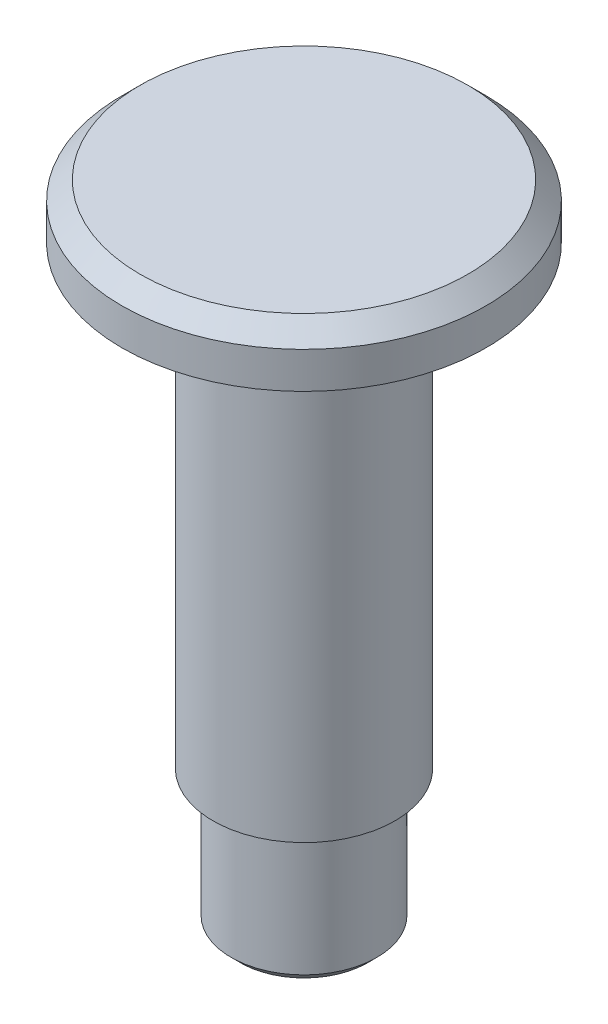
SolidWorks part; units mm, degrees
ref_plane "Plan1" through (0, 0, 0) normal (0, 0, 1) x (1, 0, 0)
ref_plane "Plan2" through (0, 0, 0) normal (0, 1, 0) x (1, 0, 0)
ref_plane "Plan3" through (0, 0, 0) normal (1, 0, 0) x (0, 0, -1)
sketch "Esquisse1" plane through (0, 0, 0) normal (0, 0, 1) x (1, 0, 0)
  line L0 (0, 0) -> (0, 100) construction
  line L1 (0, 0) -> (3.5, 0)
  line L2 (4, 0.5) -> (4, 7.5)
  line L3 (5, 7.5) -> (5, 32.5)
  line L4 (5.6, 32.5) -> (10, 32.5)
  line L5 (10, 34.5) -> (10, 32.5)
  line L7 (9, 35.5) -> (0, 35.5)
  line L8 (0, 35.5) -> (0, 0)
  line L9 (5, 7.5) -> (4.6, 7.5)
  line L10 (9, 35.5) -> (10, 34.5)
  line L11 (3.5, 0) -> (4, 0.5)
  arc A0 (4.6, 7.5) -> (4, 7.5) centre (4.3, 7.5) ccw
  arc A1 (5.6, 32.5) -> (5, 32.5) centre (5.3, 32.5) ccw
  point P3 (4, 0)
  dimension "D4" = 0.3
  dimension "D5" = 5
  dimension "D6" = 0.3
  dimension "D1" = 7.5
  dimension "D2" = 25
  dimension "D3" = 3
  dimension "D7" = 4
  dimension "D8" = 10
  dimension "D12" = 0.5
  dimension "D9" = 1
  dimension "D10" = 1
revolve "Base-Révolution" add sketch "Esquisse1" angle 360 about L0
sketch "Esquisse2" plane through (0, 35.5, 0) normal (0, 1, 0) x (-1, 0, 0)
  point P0 (0, 0)
  dimension "D10" = 0.5
